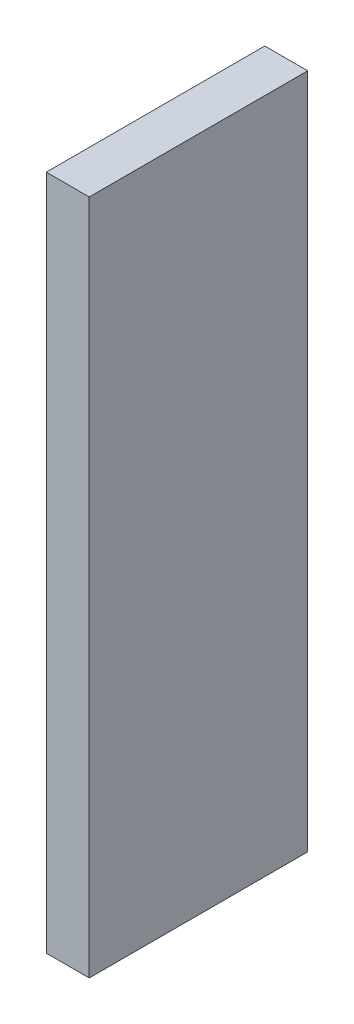
SolidWorks part; units mm, degrees
ref_plane "Front Plane" through (0, 0, 0) normal (0, 0, 1) x (1, 0, 0)
ref_plane "Top Plane" through (0, 0, 0) normal (0, 1, 0) x (1, 0, 0)
ref_plane "Right Plane" through (0, 0, 0) normal (1, 0, 0) x (0, 0, -1)
sketch "Sketch1" plane through (0, 0, 0) normal (1, 0, 0) x (0, 0, -1)
  line L1 (-16.15, -50) -> (16.15, -50)
  line L2 (-16.15, -50) -> (-16.15, 50)
  line L3 (-16.15, 50) -> (16.15, 50)
  line L4 (16.15, -50) -> (16.15, 50)
  line L5 (-16.15, -50) -> (16.15, 50) construction
  line L6 (-16.15, 50) -> (16.15, -50) construction
  point P0 (0, 0)
  dimension "D1" = 32.3
  dimension "D2" = 100
extrude "Boss-Extrude1" add sketch "Sketch1" along normal blind 6.35
